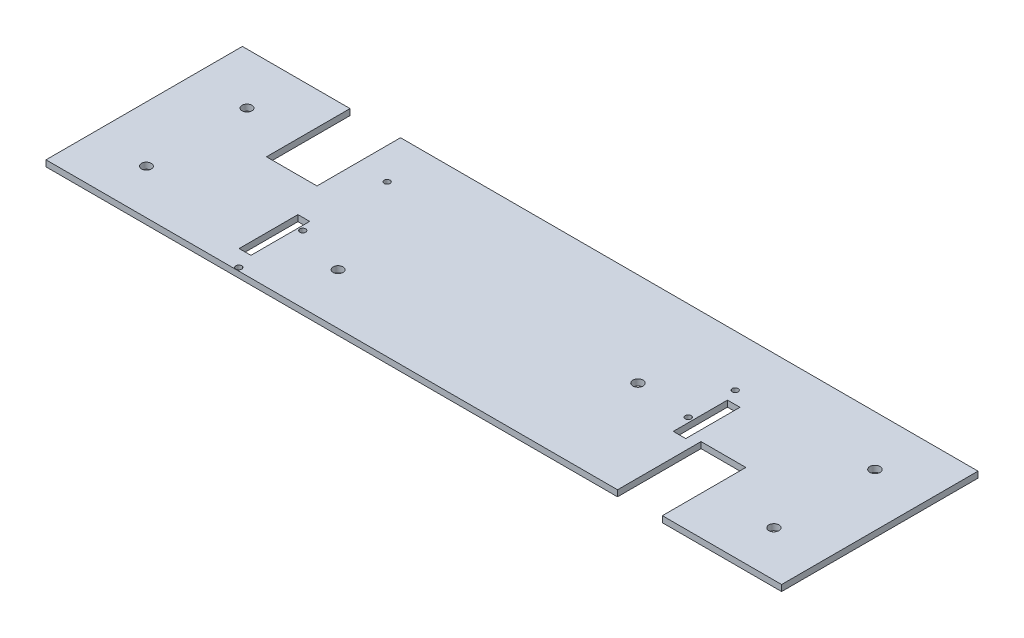
SolidWorks part; units mm, degrees
ref_plane "Front Plane" through (0, 0, 0) normal (0, 0, 1) x (1, 0, 0)
ref_plane "Top Plane" through (0, 0, 0) normal (0, 1, 0) x (1, 0, 0)
ref_plane "Right Plane" through (0, 0, 0) normal (1, 0, 0) x (0, 0, -1)
sketch "Sketch2" plane through (0, 0, 0) normal (0, 1, 0) x (1, 0, 0)
  line L1 (-191.516, -50.8) -> (191.516, -50.8)
  line L2 (-191.516, -50.8) -> (-191.516, 50.8)
  line L3 (-191.516, 50.8) -> (191.516, 50.8)
  line L4 (191.516, -50.8) -> (191.516, 50.8)
  line L5 (-191.516, -50.8) -> (191.516, 50.8) construction
  line L6 (-191.516, 50.8) -> (191.516, -50.8) construction
  point P0 (0, 0)
  dimension "D1" = 383.032
  dimension "D2" = 101.6
extrude "Boss-Extrude1" add sketch "Sketch2" along normal blind 3.175
sketch "Sketch3" plane through (0, 3.175, 0) normal (0, 1, 0) x (1, 0, 0)
  line L0 (-191.516, 24.384) -> (-160.2184, 24.384) construction
  line L1 (-191.516, 50.8) -> (-191.516, -50.8) construction
  line L2 (-160.2184, 24.384) -> (-160.2184, 50.8) construction
  line L3 (191.516, 50.8) -> (-191.516, 50.8) construction
  line L4 (-160.2184, -50.8) -> (-160.2184, -27.664) construction
  line L5 (-191.516, -50.8) -> (191.516, -50.8) construction
  line L6 (-191.516, -50.8) -> (-99.314, -50.8) construction
  line L7 (-133.35, 50.8) -> (-107.2218, 50.8)
  line L8 (-133.35, 50.8) -> (-133.35, 7.5743)
  line L9 (-133.35, 7.5743) -> (-107.2218, 7.5743)
  line L10 (-107.2218, 50.8) -> (-107.2218, 7.5743)
  line L11 (-99.314, -50.8) -> (-99.314, -40.5996) construction
  line L12 (-191.516, -50.8) -> (-91.694, -50.8) construction
  line L13 (-99.314, -40.5996) -> (-93.218, -40.5996)
  line L14 (-99.314, -40.5996) -> (-99.314, -10.1847)
  line L15 (-99.314, -10.1847) -> (-93.218, -10.1847)
  line L16 (-93.218, -40.5996) -> (-93.218, -10.1847)
  line L17 (-91.694, -50.8) -> (-90.932, -50.8) construction
  line L18 (-90.932, -50.8) -> (-90.932, 50.8) construction
  line L19 (-90.932, -50.8) -> (-90.932, -49.149) construction
  line L20 (-90.932, -47.625) -> (-90.932, -16.0763) construction
  line L21 (-90.932, -14.5523) -> (-90.932, 27.5709) construction
  line L22 (-191.516, -50.8) -> (-64.2581, -50.8) construction
  line L23 (-64.2581, -50.8) -> (-64.2581, -24.4736) construction
  circle A0 centre (-160.2184, 24.384) radius 2.54
  circle A1 centre (-160.2184, -27.664) radius 2.54
  circle A2 centre (-90.932, -49.149) radius 1.524
  circle A3 centre (-90.932, -16.0763) radius 1.524
  circle A4 centre (-90.932, 27.5709) radius 1.524
  circle A5 centre (-64.2581, -24.4736) radius 2.54
  dimension "D2" = 58.166
  dimension "D7" = 6.096
  dimension "D1" = 26.416
  dimension "D3" = 26.1282
  dimension "D4" = 99.822
  dimension "D5" = 92.202
  dimension "D6" = 1.651
extrude "Cut-Extrude1" cut sketch "Sketch3" against normal blind 5.08
sketch "Sketch4" plane through (0, 3.175, 0) normal (0, 1, 0) x (1, 0, 0)
  line L0 (191.516, 50.8) -> (164.1034, 50.8) construction
  line L1 (191.516, 50.8) -> (-107.2218, 50.8) construction
  line L2 (164.1034, 50.8) -> (164.1034, 24.8839) construction
  line L3 (164.1034, -50.8) -> (164.1034, -27.3726)
  line L4 (-191.516, -50.8) -> (191.516, -50.8) construction
  line L5 (191.516, -50.8) -> (129.828, -50.8) construction
  line L6 (191.516, -50.8) -> (64.135, -50.8) construction
  line L7 (129.828, -50.8) -> (106.634, -50.8)
  line L8 (129.828, -50.8) -> (129.828, -7.6006)
  line L9 (129.828, -7.6006) -> (106.634, -7.6006)
  line L10 (106.634, -50.8) -> (106.634, -7.6006)
  line L11 (64.135, -50.8) -> (64.135, 2.286) construction
  line L12 (191.516, 50.8) -> (101.346, 50.8) construction
  line L13 (101.346, 50.8) -> (101.346, 17.812) construction
  line L14 (191.516, 50.8) -> (92.456, 50.8) construction
  line L15 (101.346, 17.812) -> (94.892, 17.812)
  line L16 (101.346, 17.812) -> (101.346, -10.2226)
  line L17 (101.346, -10.2226) -> (94.892, -10.2226)
  line L18 (94.892, 17.812) -> (94.892, -10.2226)
  line L19 (92.456, 50.8) -> (92.456, 24.257) construction
  line L20 (92.456, 22.733) -> (92.456, -1.524) construction
  circle A0 centre (164.1034, 24.8839) radius 2.6536
  circle A1 centre (164.1034, -27.3726) radius 2.6141
  circle A2 centre (64.135, 2.286) radius 2.6573
  circle A3 centre (92.456, 24.257) radius 1.524
  circle A4 centre (92.456, 0) radius 1.524
  dimension "D1" = 90.17
  dimension "D3" = 24.257
  dimension "D2" = 99.06
  dimension "D4" = 26.543
extrude "Cut-Extrude2" cut sketch "Sketch4" against normal blind 5.08
sketch "Sketch5" plane through (0, 3.175, 0) normal (0, 1, 0) x (1, 0, 0)
  line L1 (-200.8115, 60.1542) -> (-189.0305, 60.1542)
  line L2 (-200.8115, 60.1542) -> (-200.8115, -56.2272)
  line L3 (-200.8115, -56.2272) -> (-189.0305, -56.2272)
  line L4 (-189.0305, 60.1542) -> (-189.0305, -56.2272)
extrude "Cut-Extrude3" cut sketch "Sketch5" against normal blind 6.35
